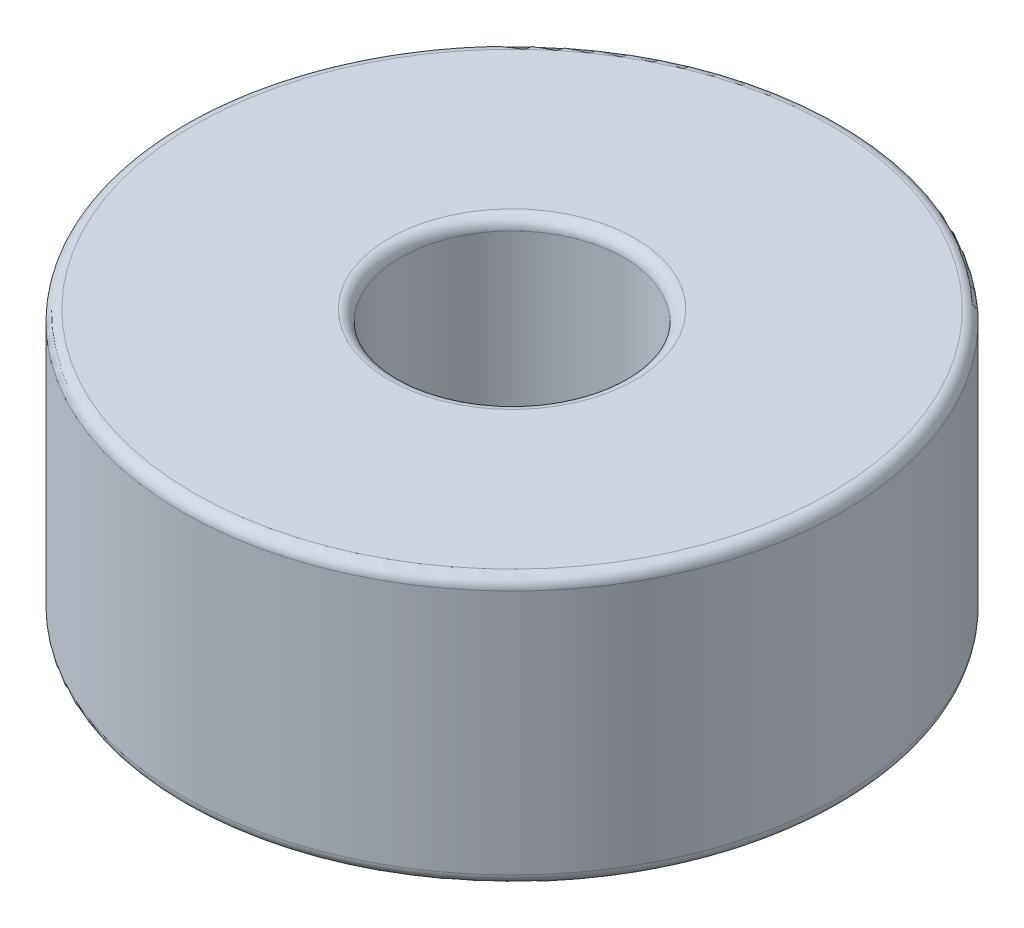
SolidWorks part; units mm, degrees
material "Plain Carbon Steel"
ref_plane "Front Plane" through (0, 0, 0) normal (0, 0, 1) x (1, 0, 0)
ref_plane "Top Plane" through (0, 0, 0) normal (0, 1, 0) x (1, 0, 0)
ref_plane "Right Plane" through (0, 0, 0) normal (1, 0, 0) x (0, 0, -1)
sketch "Sketch1" plane through (0, 0, 0) normal (0, 1, 0) x (1, 0, 0)
  circle A0 centre (0, 0) radius 2.95
  dimension "D1" = 5.9
extrude "Boss-Extrude1" add sketch "Sketch1" along normal blind 2.4
sketch "Sketch2" plane through (0, 2.4, 0) normal (0, 1, 0) x (1, 0, 0)
  circle A0 centre (0, 0) radius 1
  dimension "D1" = 2
extrude "Cut-Extrude1" cut sketch "Sketch2" against normal through all
fillet "Fillet1" radius 0.1 4 edges at (0, 2.4, 1) (0, 0, 2.95) (0, 2.4, 2.95) (0, 0, 1)
